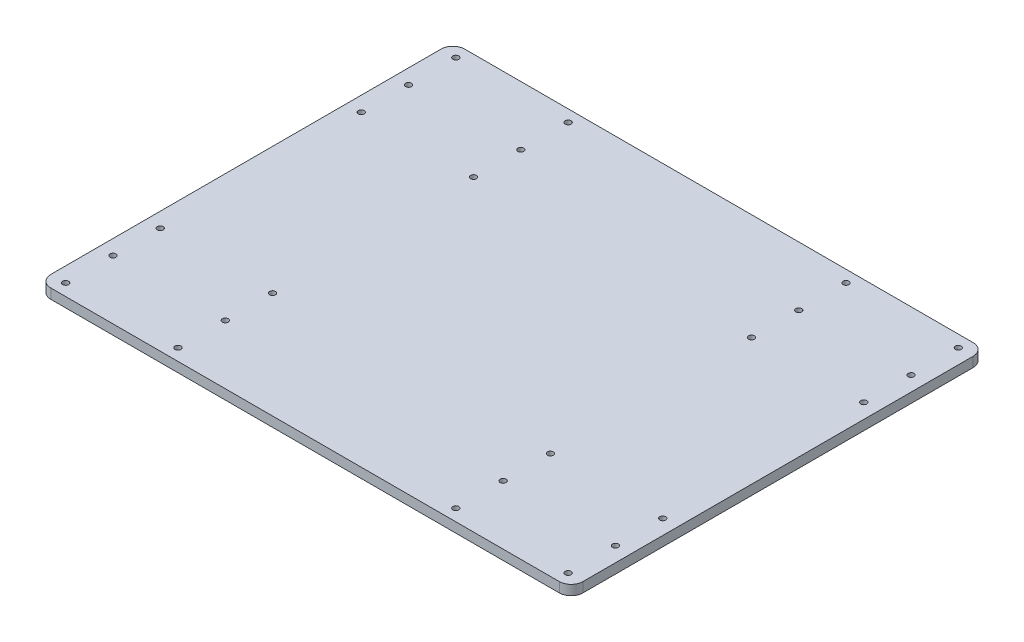
SolidWorks part; units mm, degrees
ref_plane "Front Plane" through (0, 0, 0) normal (0, 0, 1) x (1, 0, 0)
ref_plane "Top Plane" through (0, 0, 0) normal (0, 1, 0) x (1, 0, 0)
ref_plane "Right Plane" through (0, 0, 0) normal (1, 0, 0) x (0, 0, -1)
sketch "Sketch1" plane through (0, 0, 0) normal (0, 1, 0) x (1, 0, 0)
  line L0 (-127.5, 105) -> (-127.5, -105) construction
  line L1 (-129, -105) -> (129, -105)
  line L2 (-135, -99) -> (-135, 99)
  line L3 (-129, 105) -> (129, 105)
  line L4 (135, -99) -> (135, 99)
  line L5 (-135, -105) -> (135, 105) construction
  line L6 (-135, 105) -> (135, -105) construction
  line L8 (0, 105) -> (0, -105) construction
  line L9 (-135, 0) -> (135, 0) construction
  circle A0 centre (-127.5, 99) radius 1.5
  circle A1 centre (-127.5, 75) radius 1.5
  circle A2 centre (-127.5, 51) radius 1.5
  circle A3 centre (-70.5, 99) radius 1.5
  circle A4 centre (-70.5, 75) radius 1.5
  circle A5 centre (-70.5, 51) radius 1.5
  circle A6 centre (70.5, 51) radius 1.5
  circle A7 centre (70.5, 75) radius 1.5
  circle A8 centre (70.5, 99) radius 1.5
  circle A9 centre (127.5, 51) radius 1.5
  circle A10 centre (127.5, 75) radius 1.5
  circle A11 centre (127.5, 99) radius 1.5
  circle A12 centre (127.5, -99) radius 1.5
  circle A13 centre (127.5, -75) radius 1.5
  circle A14 centre (127.5, -51) radius 1.5
  circle A15 centre (70.5, -99) radius 1.5
  circle A16 centre (70.5, -75) radius 1.5
  circle A17 centre (70.5, -51) radius 1.5
  circle A18 centre (-70.5, -51) radius 1.5
  circle A19 centre (-70.5, -75) radius 1.5
  circle A20 centre (-70.5, -99) radius 1.5
  circle A21 centre (-127.5, -51) radius 1.5
  circle A22 centre (-127.5, -75) radius 1.5
  circle A23 centre (-127.5, -99) radius 1.5
  arc A37 (129, 105) -> (135, 99) centre (129, 99) cw
  arc A38 (135, -99) -> (129, -105) centre (129, -99) cw
  arc A39 (-129, -105) -> (-135, -99) centre (-129, -99) cw
  arc A40 (-135, 99) -> (-129, 105) centre (-129, 99) cw
  point P0 (0, 0)
  point P59 (0, 0)
  point P88 (0, 0)
  point P98 (0, 0)
  dimension "D5" = 3
  dimension "D14" = 57
  dimension "D19" = 6
  dimension "D1" = 270
  dimension "D2" = 210
  dimension "D3" = 7.5
  dimension "D4" = 3
  dimension "D6" = 6
  dimension "D13" = 24
  dimension "D7" = 2
extrude "Boss-Extrude1" add sketch "Sketch1" along normal blind 5
